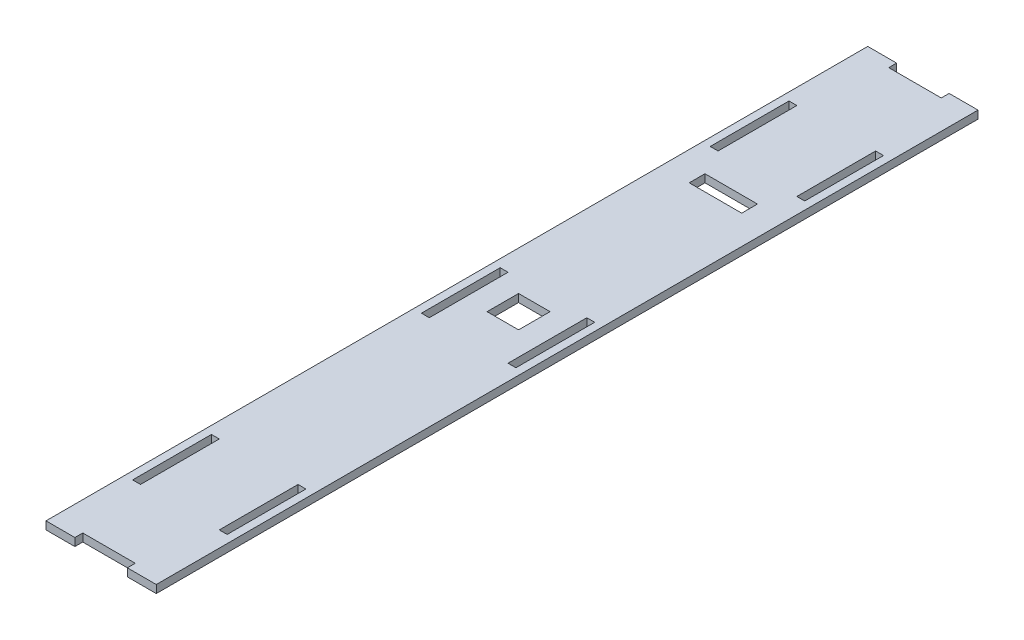
SolidWorks part; units mm, degrees
material "ABS"
ref_plane "Front Plane" through (0, 0, 0) normal (0, 0, 1) x (1, 0, 0)
ref_plane "Top Plane" through (0, 0, 0) normal (0, 1, 0) x (1, 0, 0)
ref_plane "Right Plane" through (0, 0, 0) normal (1, 0, 0) x (0, 0, -1)
sketch "Sketch1" plane through (0, 0, 0) normal (0, 1, 0) x (1, 0, 0)
  line L0 (21, 0) -> (21, 146.9709) construction
  line L1 (0, 0) -> (11, 0)
  line L2 (0, 0) -> (0, 313)
  line L3 (0, 313) -> (42, 313)
  line L4 (42, 0) -> (42, 313)
  line L5 (36, 60) -> (39, 60)
  line L6 (36, 60) -> (36, 30)
  line L7 (36, 30) -> (39, 30)
  line L8 (39, 60) -> (39, 30)
  line L9 (36, 170) -> (39, 170)
  line L10 (36, 170) -> (36, 140)
  line L11 (36, 140) -> (39, 140)
  line L12 (39, 170) -> (39, 140)
  line L13 (36, 280) -> (39, 280)
  line L14 (36, 280) -> (36, 250)
  line L15 (36, 250) -> (39, 250)
  line L16 (39, 280) -> (39, 250)
  line L17 (11, 313) -> (31, 313)
  line L18 (11, 313) -> (11, 310)
  line L19 (11, 310) -> (31, 310)
  line L20 (31, 313) -> (31, 310)
  line L21 (6, 30) -> (3, 30)
  line L22 (3, 60) -> (3, 30)
  line L23 (6, 60) -> (3, 60)
  line L24 (6, 60) -> (6, 30)
  line L25 (6, 170) -> (3, 170)
  line L26 (6, 140) -> (3, 140)
  line L27 (3, 170) -> (3, 140)
  line L28 (6, 170) -> (6, 140)
  line L29 (6, 250) -> (3, 250)
  line L30 (6, 280) -> (6, 250)
  line L31 (3, 280) -> (3, 250)
  line L32 (6, 280) -> (3, 280)
  line L33 (31, 0) -> (42, 0)
  line L35 (11, 0) -> (11, 3)
  line L36 (11, 3) -> (31, 3)
  line L37 (31, 0) -> (31, 3)
  line L39 (15, 165) -> (27, 165)
  line L40 (15, 165) -> (15, 153)
  line L41 (15, 153) -> (27, 153)
  line L42 (27, 165) -> (27, 153)
  line L43 (11, 240) -> (31, 240)
  line L44 (11, 240) -> (11, 234)
  line L45 (11, 234) -> (31, 234)
  line L46 (31, 240) -> (31, 234)
  point P43 (36.5, 0)
  dimension "D1" = 313
  dimension "D2" = 42
  dimension "D3" = 20
  dimension "D4" = 3
  dimension "D5" = 11
  dimension "D6" = 30
  dimension "D7" = 3
  dimension "D8" = 3
  dimension "D9" = 80
  dimension "D10" = 30
  dimension "D11" = 3
  dimension "D12" = 3
  dimension "D13" = 30
  dimension "D14" = 3
  dimension "D15" = 3
  dimension "D16" = 80
  dimension "D17" = 30
  dimension "D18" = 3
  dimension "D19" = 20
  dimension "D20" = 11
  dimension "D21" = 12
  dimension "D22" = 12
  dimension "D23" = 15
  dimension "D24" = 153
  dimension "D25" = 6
  dimension "D26" = 20
  dimension "D27" = 70
  dimension "D28" = 11
extrude "Boss-Extrude1" add sketch "Sketch1" along normal blind 3
